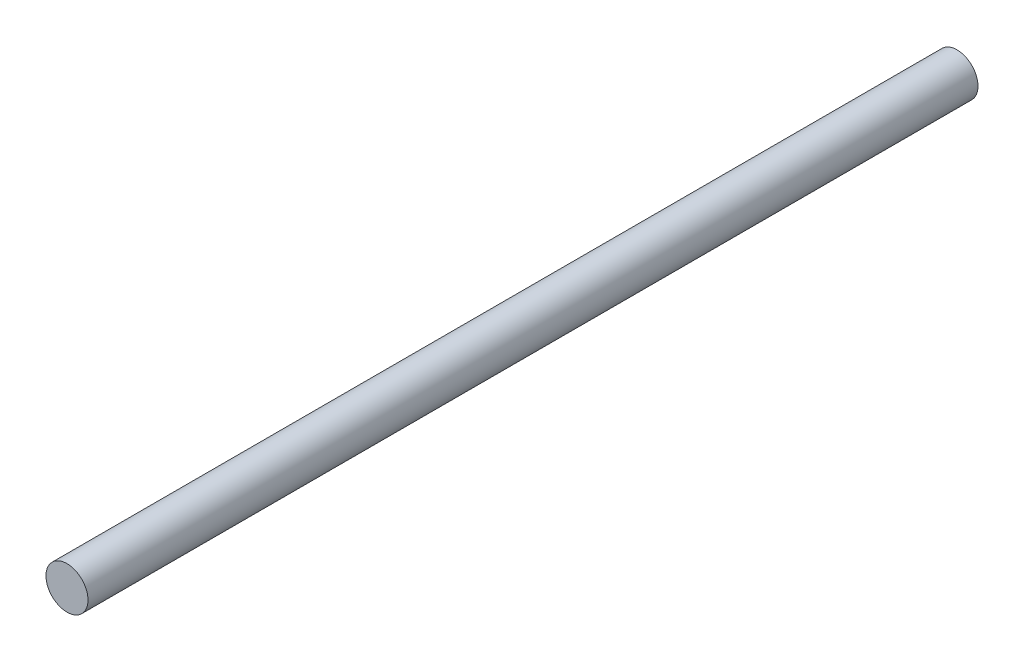
SolidWorks part; units mm, degrees
material "Alloy Steel"
ref_plane "Front Plane" through (0, 0, 0) normal (0, 0, 1) x (1, 0, 0)
ref_plane "Top Plane" through (0, 0, 0) normal (0, 1, 0) x (1, 0, 0)
ref_plane "Right Plane" through (0, 0, 0) normal (1, 0, 0) x (0, 0, -1)
sketch "Sketch1" plane through (0, 0, 0) normal (0, 0, 1) x (1, 0, 0)
  circle A0 centre (0, 0) radius 3
  dimension "D1" = 6
extrude "Boss-Extrude1" add sketch "Sketch1" along normal blind 127 contours A0
